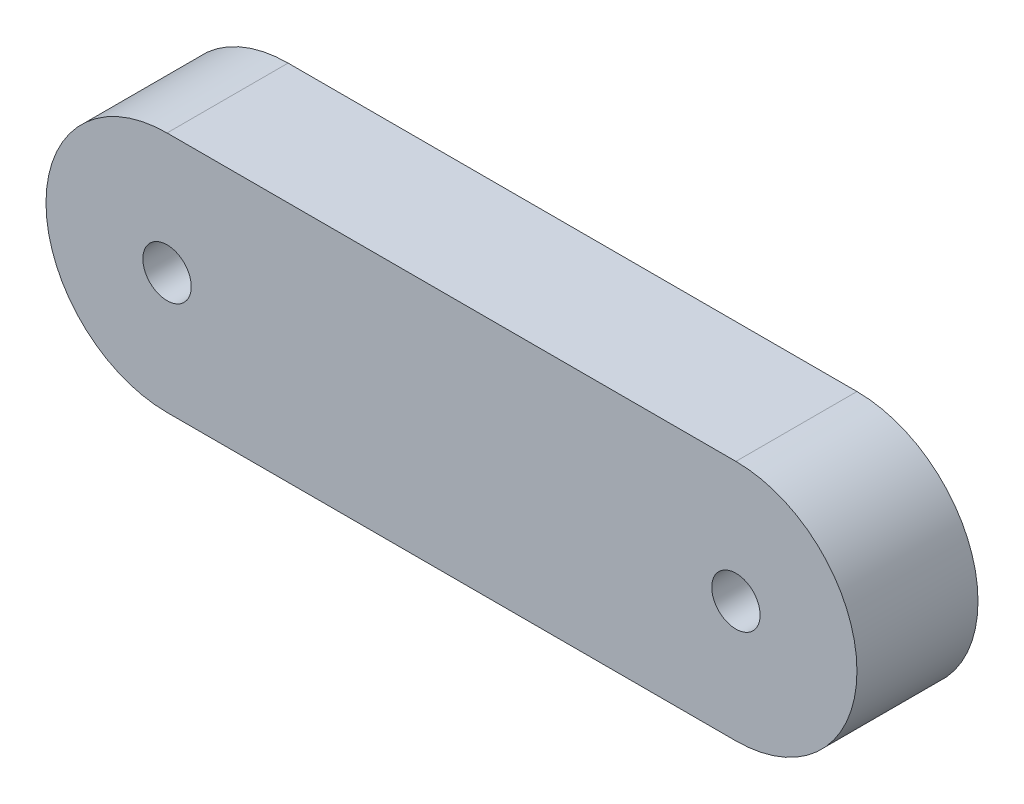
SolidWorks part; units mm, degrees
ref_plane "Front Plane" through (0, 0, 0) normal (0, 0, 1) x (1, 0, 0)
ref_plane "Top Plane" through (0, 0, 0) normal (0, 1, 0) x (1, 0, 0)
ref_plane "Right Plane" through (0, 0, 0) normal (1, 0, 0) x (0, 0, -1)
sketch "Sketch1" plane through (0, 0, 0) normal (0, 0, 1) x (1, 0, 0)
  line L0 (-146.2328, 7.5042) -> (-193.2328, 7.5042) construction
  line L1 (-146.2328, -2.4958) -> (-193.2328, -2.4958)
  line L2 (-146.2328, 17.5042) -> (-193.2328, 17.5042)
  arc A0 (-146.2328, -2.4958) -> (-146.2328, 17.5042) centre (-146.2328, 7.5042) ccw
  arc A1 (-193.2328, 17.5042) -> (-193.2328, -2.4958) centre (-193.2328, 7.5042) ccw
  circle A2 centre (-193.2328, 7.5042) radius 2
  circle A3 centre (-146.2328, 7.5042) radius 2
  point P2 (-169.7328, 7.5042)
  dimension "D2" = 10
  dimension "D1" = 47
extrude "Boss-Extrude1" add sketch "Sketch1" along normal blind 10
